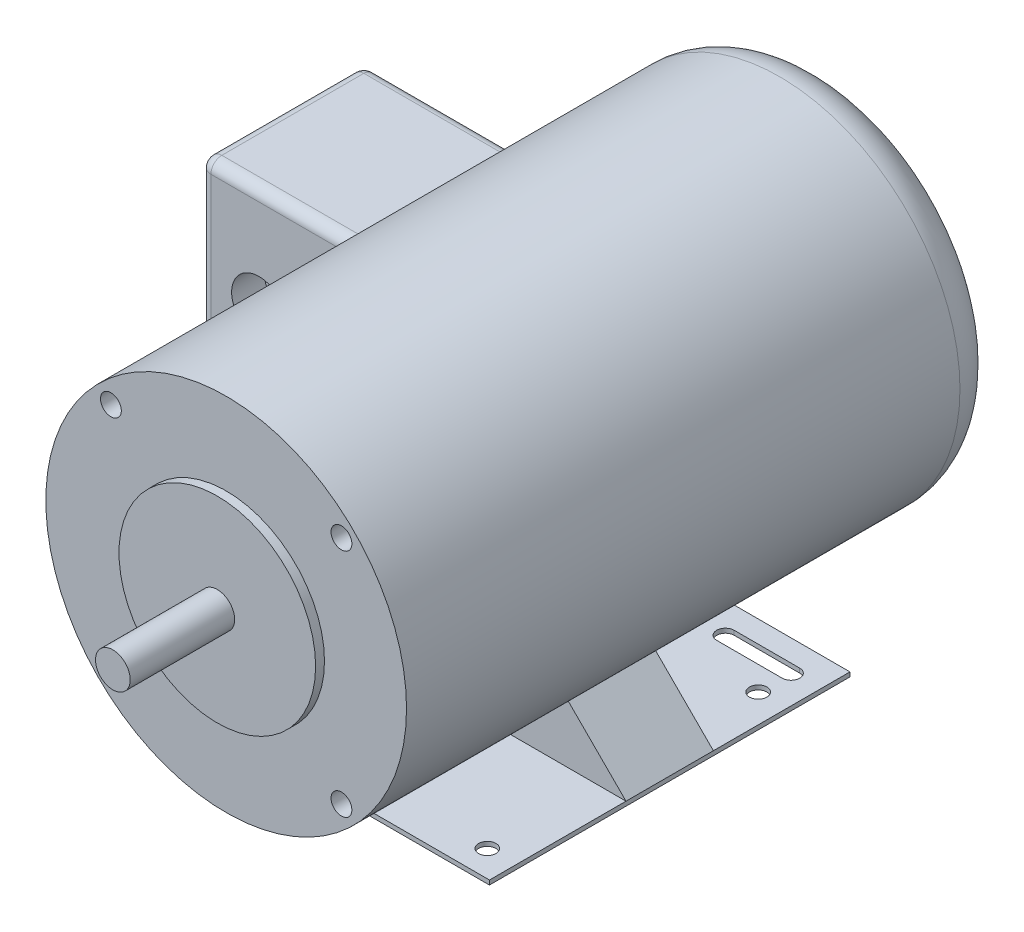
SolidWorks part; units mm, degrees
ref_plane "Front Plane" through (0, 0, 0) normal (0, 0, 1) x (1, 0, 0)
ref_plane "Top Plane" through (0, 0, 0) normal (0, 1, 0) x (1, 0, 0)
ref_plane "Right Plane" through (0, 0, 0) normal (1, 0, 0) x (0, 0, -1)
sketch "Sketch1" plane through (0, 0, 0) normal (0, 0, 1) x (1, 0, 0)
  circle A0 centre (0, 0) radius 82.55
  dimension "D1" = 165.1
extrude "Boss-Extrude1" add sketch "Sketch1" along normal blind 273.304
sketch "Sketch2" plane through (0, 0, 273.304) normal (0, 0, 1) x (1, 0, 0)
  circle A0 centre (0, 0) radius 45
  dimension "D1" = 90
extrude "Boss-Extrude2" add sketch "Sketch2" along normal blind 4.064
sketch "Sketch3" plane through (0, 0, 277.368) normal (0, 0, 1) x (1, 0, 0)
  circle A0 centre (0, 0) radius 7.94
  dimension "D1" = 15.88
extrude "Boss-Extrude3" add sketch "Sketch3" along normal blind 47.8
ref_plane "Mounting Plane" through (0, -89, 0) normal (0, 1, 0) x (1, 0, 0)
sketch "Sketch5" plane through (0, -89, 0) normal (0, 1, 0) x (1, 0, 0)
  line L0 (0, -322.5255) -> (0, 0) construction
  line L1 (-82.5, -235.304) -> (82.5, -235.304)
  line L2 (-82.5, -235.304) -> (-82.5, -70.304)
  line L3 (-82.5, -70.304) -> (82.5, -70.304)
  line L4 (82.5, -235.304) -> (82.5, -70.304)
  line L5 (156.5028, -152.804) -> (-155.9152, -152.804) construction
  line L7 (-82.55, -273.304) -> (82.55, -273.304) construction
  line L8 (69.5, -99.304) -> (-69.5, -99.304) construction
  line L9 (69.5, -223.304) -> (-69.5, -223.304) construction
  line L10 (69.5, -223.304) -> (69.5, -99.304) construction
  line L11 (69.5, -84.304) -> (39.5, -84.304) construction
  line L12 (69.5, -88.304) -> (39.5, -88.304)
  line L13 (69.5, -80.304) -> (39.5, -80.304)
  line L14 (-69.5, -84.304) -> (-39.5, -84.304) construction
  line L15 (-69.5, -88.304) -> (-39.5, -88.304)
  line L16 (-69.5, -80.304) -> (-39.5, -80.304)
  circle A0 centre (69.5, -223.304) radius 4
  circle A1 centre (69.5, -99.304) radius 4
  circle A2 centre (-69.5, -99.304) radius 4
  circle A3 centre (-69.5, -223.304) radius 4
  arc A4 (69.5, -88.304) -> (69.5, -80.304) centre (69.5, -84.304) ccw
  arc A5 (39.5, -80.304) -> (39.5, -88.304) centre (39.5, -84.304) ccw
  arc A6 (-69.5, -88.304) -> (-69.5, -80.304) centre (-69.5, -84.304) cw
  arc A7 (-39.5, -80.304) -> (-39.5, -88.304) centre (-39.5, -84.304) cw
  point P21 (54.5, -84.304)
  point P28 (-54.5, -84.304)
  dimension "D3" = 8
  dimension "D8" = 8
  dimension "D9" = 8
  dimension "D10" = 8
  dimension "D11" = 4
  dimension "D1" = 165
  dimension "D2" = 165
  dimension "D5" = 12
  dimension "D6" = 50
  dimension "D7" = 124
  dimension "D4" = 139
  dimension "D12" = 14
  dimension "D13" = 30
extrude "Boss-Extrude4" add sketch "Sketch5" along normal blind 2 separate body
ref_plane "Plane2" through (-137, 0, 0) normal (1, 0, 0) x (0, 0, -1)
sketch "Sketch6" plane through (-137, 0, 0) normal (1, 0, 0) x (0, 0, -1)
  line L0 (0, 0) -> (-255.3159, 0) construction
  line L1 (-73.304, 47) -> (-148.304, 47)
  line L2 (-73.304, 47) -> (-73.304, -47)
  line L3 (-73.304, -47) -> (-148.304, -47)
  line L4 (-148.304, 47) -> (-148.304, -47)
  line L5 (-273.304, 45) -> (-273.304, -45) construction
  dimension "D1" = 94
  dimension "D2" = 75
  dimension "D3" = 125
extrude "Boss-Extrude5" add sketch "Sketch6" along normal up to next separate body
sketch "Sketch7" plane through (0, 0, 273.304) normal (0, 0, 1) x (1, 0, 0)
  line L1 (-79.6993, -79.6993) -> (81.1874, 81.1874) construction
  line L2 (0, 0) -> (135.1684, 0) construction
  line L3 (0, 0) -> (0, 75.6467) construction
  line L4 (144.8262, -15.5655) -> (144.8262, -16.2809) construction
  circle A0 centre (0, 0) radius 74.615 construction
  circle A1 centre (52.7608, 52.7608) radius 4.7625
  circle A2 centre (52.7608, -52.7608) radius 4.7625
  circle A3 centre (-52.7608, -52.7608) radius 4.7625
  circle A4 centre (-52.7608, 52.7608) radius 4.7625
  dimension "D3" = 149.23
  dimension "D4" = 9.525
  dimension "D2" = 45
extrude "Cut-Extrude1" cut sketch "Sketch7" against normal blind 15
sketch "Sketch8" plane through (0, 0, 148.304) normal (0, 0, 1) x (1, 0, 0)
  line L0 (-110, 0) -> (0, 0) construction
  circle A0 centre (-110, 0) radius 12.5
  dimension "D1" = 25
  dimension "D2" = 110
extrude "Cut-Extrude2" cut sketch "Sketch8" against normal blind 15
ref_plane "Plane3" through (0, 0, 152.804) normal (0, 0, 1) x (1, 0, 0)
sketch "Sketch9" plane through (0, 0, 152.804) normal (0, 0, 1) x (1, 0, 0)
  line L0 (-56.0783, -60.5783) -> (-82.5, -87)
  line L1 (-82.5, -87) -> (82.5, -87)
  line L2 (82.5, -87) -> (56.0783, -60.5783)
  circle A0 centre (0, 0) radius 82.55 construction
  arc A1 (-56.0783, -60.5783) -> (56.0783, -60.5783) centre (0, 0) ccw
  dimension "D1" = 45
extrude "Boss-Extrude6" add sketch "Sketch9" along normal blind 20 and the other way blind 20
fillet "Fillet1" radius 5 8 edges at (-137, 47, 110.804) (-137, 0, 148.304) (-137, -47, 110.804) (-137, 0, 73.304) (-102.4319, -47, 73.304) (-102.4319, -47, 148.304) (-102.4319, 47, 73.304) (-102.4319, 47, 148.304)
fillet "Fillet2" radius 20 1 edges at (82.55, 0, 0)
equation "\"D8@Sketch5\"=\"D3@Sketch5\""
equation "\"D9@Sketch5\"=\"D3@Sketch5\""
equation "\"D10@Sketch5\"=\"D3@Sketch5\""
